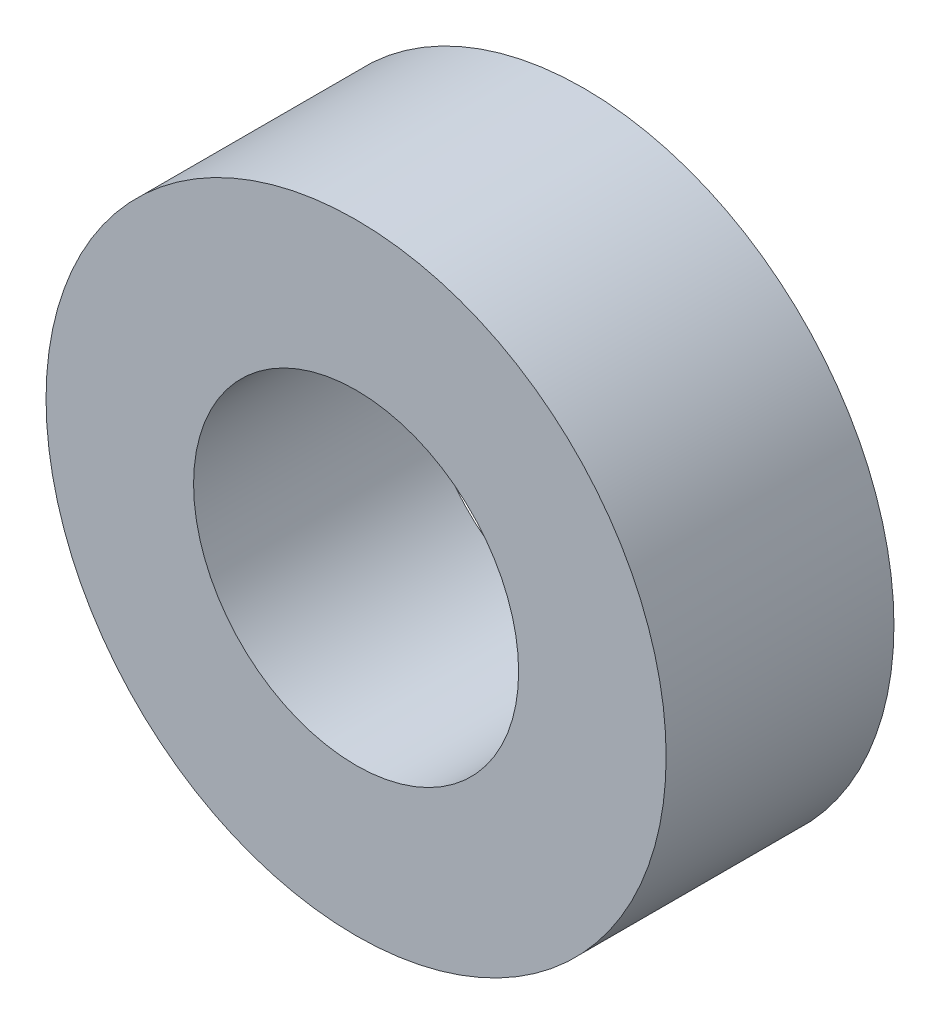
SolidWorks part; units mm, degrees
ref_plane "Front Plane" through (0, 0, 0) normal (0, 0, 1) x (1, 0, 0)
ref_plane "Top Plane" through (0, 0, 0) normal (0, 1, 0) x (1, 0, 0)
ref_plane "Right Plane" through (0, 0, 0) normal (1, 0, 0) x (0, 0, -1)
sketch "Sketch1" plane through (0, 0, 0) normal (0, 0, 1) x (1, 0, 0)
  circle A0 centre (0, 0) radius 15.1423
  dimension "D1" = 30.2846
extrude "Boss-Extrude1" add sketch "Sketch1" along normal blind 11.1252
sketch "Sketch2" plane through (0, 0, 0) normal (0, 0, -1) x (-1, 0, 0)
  circle A0 centre (0, 0) radius 7.9375
  dimension "D1" = 15.875
extrude "Cut-Extrude1" cut sketch "Sketch2" against normal up to surface (11.1252 mm away) up to face at (15.1423, 0, 11.1252)
